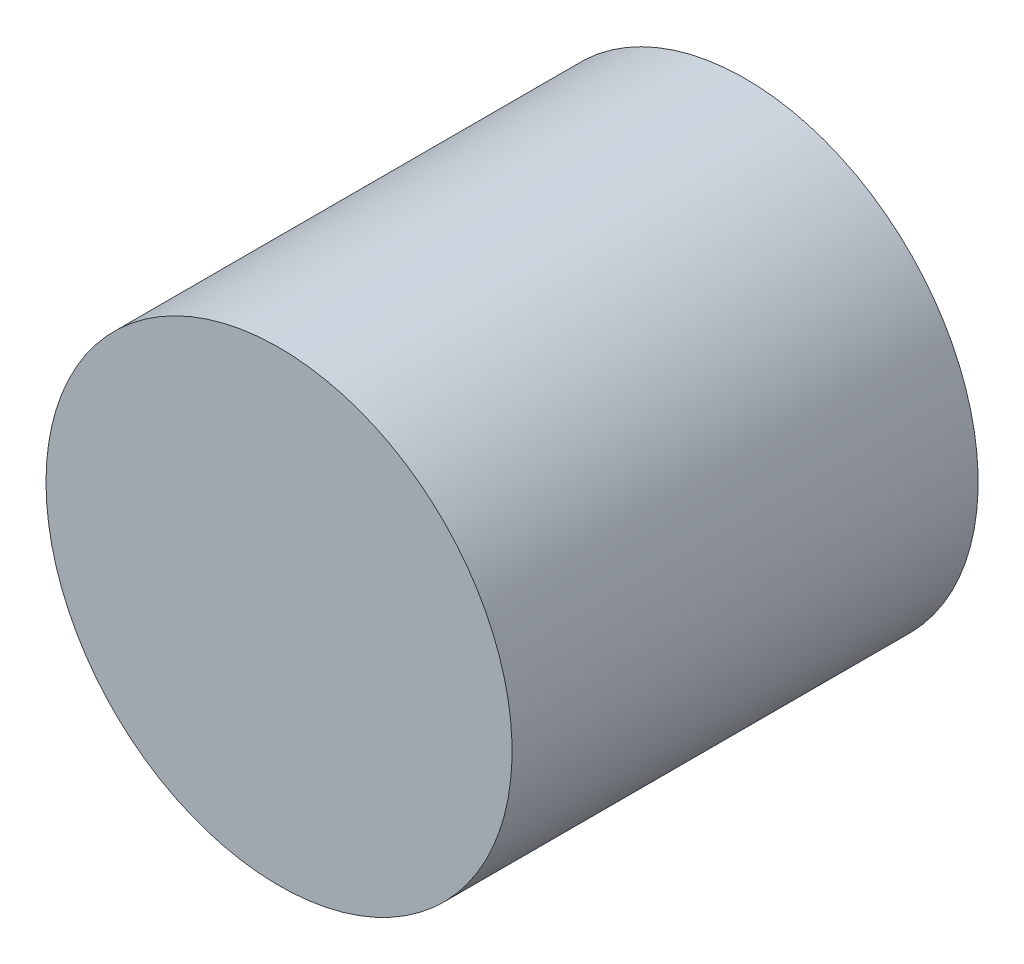
SolidWorks part; units mm, degrees
ref_plane "Front Plane" through (0, 0, 0) normal (0, 0, 1) x (1, 0, 0)
ref_plane "Top Plane" through (0, 0, 0) normal (0, 1, 0) x (1, 0, 0)
ref_plane "Right Plane" through (0, 0, 0) normal (1, 0, 0) x (0, 0, -1)
other "Configuration Table"
sketch "Sketch1" plane through (0, 0, 0) normal (0, 0, 1) x (1, 0, 0)
  circle A0 centre (0, 0) radius 30
extrude "Extrude1" add sketch "Sketch1" along normal blind 60
sketch "Sketch2" [suppressed] plane through (0, 0, 60) normal (0, 0, 1) x (1, 0, 0)
  line L1 (-10, -10) -> (10, -10)
  line L2 (-10, -10) -> (-10, 10)
  line L3 (-10, 10) -> (10, 10)
  line L4 (10, -10) -> (10, 10)
  line L5 (-10, -10) -> (10, 10) construction
  line L6 (-10, 10) -> (10, -10) construction
  point P0 (0, 0)
extrude "Extrude2" [suppressed] cut sketch "Sketch2" against normal through all
